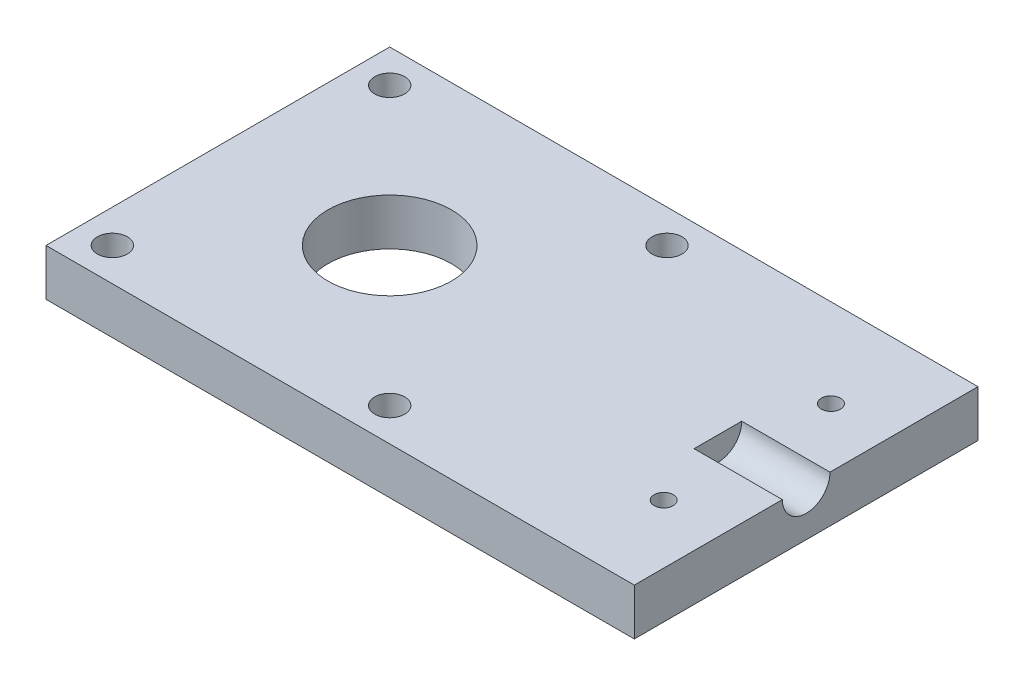
SolidWorks part; units mm, degrees
ref_plane "Top Plane" through (0, 0, 0) normal (0, 0, 1) x (1, 0, 0)
ref_plane "Front Plane" through (0, 0, 0) normal (0, 1, 0) x (1, 0, 0)
ref_plane "Right Plane" through (0, 0, 0) normal (1, 0, 0) x (0, 0, -1)
sketch "Sketch1" plane through (0, -110.0687, 0) normal (0, -1, 0) x (1, 0, 0)
  line L0 (85.5067, 85.8191) -> (85.5067, 57.3991) construction
  line L1 (-4.4933, 100.8191) -> (95.5067, 100.8191)
  line L2 (-4.4933, 100.8191) -> (-4.4933, 42.3991)
  line L3 (-4.4933, 42.3991) -> (95.5067, 42.3991)
  line L4 (95.5067, 100.8191) -> (95.5067, 42.3991)
  circle A0 centre (1.1467, 95.1791) radius 2.55
  circle A1 centre (1.1467, 48.0391) radius 2.55
  circle A2 centre (48.2867, 48.0391) radius 2.55
  circle A3 centre (48.2867, 95.1791) radius 2.55
  circle A4 centre (1.1467, 95.1791) radius 2.1 construction
  circle A5 centre (1.1467, 48.0391) radius 2.1 construction
  circle A6 centre (48.2867, 48.0391) radius 2.1 construction
  circle A7 centre (48.2867, 95.1791) radius 2.1 construction
  circle A10 centre (85.5067, 85.8191) radius 1.625
  circle A11 centre (85.5067, 57.3991) radius 1.625
  circle A14 centre (24.7167, 71.6091) radius 10.5
  circle A15 centre (24.7167, 71.6091) radius 10.5
  point P29 (-4.4933, 71.6091)
  point P30 (85.5067, 71.6091)
  dimension "D1" = 5.1
  dimension "D2" = 3.25
  dimension "D3" = 15
  dimension "D4" = 100
  dimension "D5" = 10
  dimension "D6" = 0.5
extrude "Boss-Extrude1" add sketch "Sketch1" along normal blind 7.9375
cosmetic thread "Cosmetic Thread3" parameters "D2"=4
cosmetic thread "Cosmetic Thread4" parameters "D2"=4
ref_plane "Plane1" through (0, -114.0374, 0) normal (0, -1, 0) x (-1, 0, 0)
extrude "Cut-Extrude1" cut sketch "Sketch2" against normal blind 15
sketch "Sketch2" plane through (95.5067, -1.5875, 13.9181) normal (1, 0, 0) x (0, 0, -1)
  circle A0 centre (-57.691, -108.4812) radius 4.05
